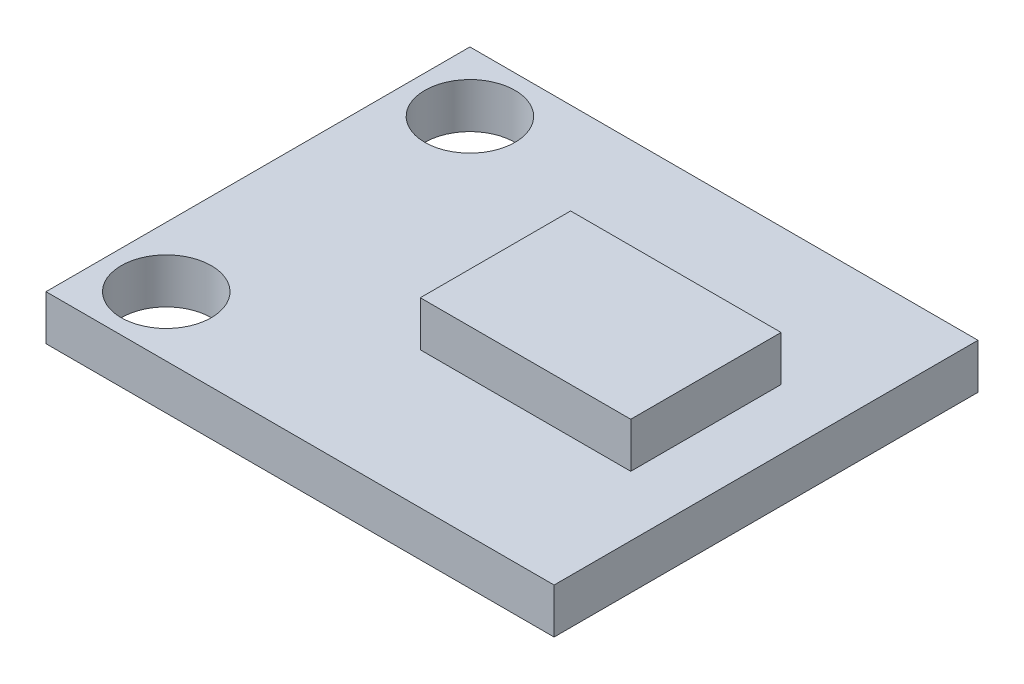
SolidWorks part; units mm, degrees
ref_plane "Front Plane" through (0, 0, 0) normal (0, 0, 1) x (1, 0, 0)
ref_plane "Top Plane" through (0, 0, 0) normal (0, 1, 0) x (1, 0, 0)
ref_plane "Right Plane" through (0, 0, 0) normal (1, 0, 0) x (0, 0, -1)
sketch "Sketch1" plane through (0, 0, 0) normal (0, 1, 0) x (1, 0, 0)
  line L1 (-8.45, 7.05) -> (8.45, 7.05)
  line L2 (-8.45, 7.05) -> (-8.45, -7.05)
  line L3 (-8.45, -7.05) -> (8.45, -7.05)
  line L4 (8.45, 7.05) -> (8.45, -7.05)
  line L5 (-8.45, 7.05) -> (8.45, -7.05) construction
  line L6 (-8.45, -7.05) -> (8.45, 7.05) construction
  line L7 (-55, 0) -> (55, 0) construction
  circle A0 centre (-6.45, 5.05) radius 1.5
  circle A2 centre (-6.45, -5.05) radius 1.5
  point P0 (0, 0)
  dimension "D3" = 3
  dimension "D1" = 16.9
  dimension "D2" = 14.1
  dimension "D4" = 2
  dimension "D5" = 2
extrude "Boss-Extrude1" add sketch "Sketch1" along normal blind 1.5
sketch "Sketch2" plane through (0, 1.5, 0) normal (0, 1, 0) x (1, 0, 0)
  line L0 (8.45, -7.05) -> (8.45, 7.05) construction
  line L1 (-0.55, 2.5) -> (6.45, 2.5)
  line L2 (-0.55, 2.5) -> (-0.55, -2.5)
  line L3 (-0.55, -2.5) -> (6.45, -2.5)
  line L4 (6.45, 2.5) -> (6.45, -2.5)
  line L5 (-0.55, 2.5) -> (6.45, -2.5) construction
  line L6 (-0.55, -2.5) -> (6.45, 2.5) construction
  point P0 (2.95, 0)
  dimension "D1" = 7
  dimension "D2" = 5
  dimension "D3" = 2
extrude "Boss-Extrude2" add sketch "Sketch2" along normal blind 1.5
